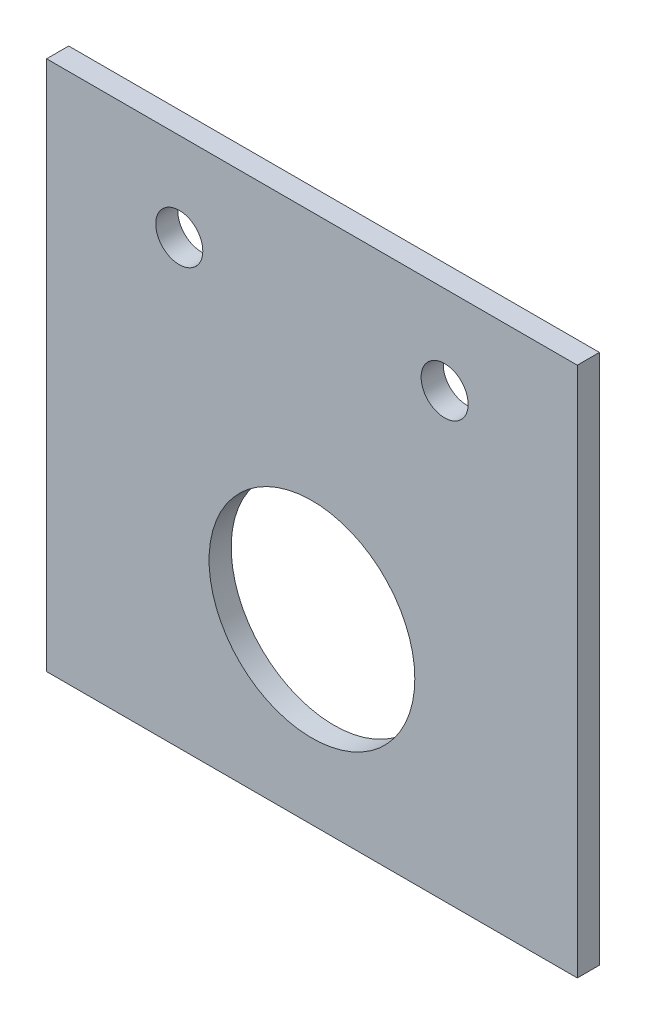
SolidWorks part; units mm, degrees
ref_plane "Front Plane" through (0, 0, 0) normal (0, 0, 1) x (1, 0, 0)
ref_plane "Top Plane" through (0, 0, 0) normal (0, 1, 0) x (1, 0, 0)
ref_plane "Right Plane" through (0, 0, 0) normal (1, 0, 0) x (0, 0, -1)
sketch "Sketch1" plane through (0, 0, 0) normal (0, 0, 1) x (1, 0, 0)
  line L1 (38.1, -38.1) -> (-38.1, -38.1)
  line L2 (38.1, -38.1) -> (38.1, 38.1)
  line L3 (38.1, 38.1) -> (-38.1, 38.1)
  line L4 (-38.1, -38.1) -> (-38.1, 38.1)
  line L5 (38.1, -38.1) -> (-38.1, 38.1) construction
  line L6 (38.1, 38.1) -> (-38.1, -38.1) construction
  point P0 (0, 0)
  dimension "D1" = 76.2
  dimension "D2" = 76.2
extrude "Boss-Extrude1" add sketch "Sketch1" along normal blind 3.175
hole_wizard "1/4 Clearance Hole1" positions "Sketch2" profile "Sketch3" hole size "1/4" standard "ANSI Inch" end condition through all
sketch "Sketch2" plane through (0, 0, 3.175) normal (0, 0, 1) x (1, 0, 0)
  line L0 (-38.1, 25.4) -> (38.1, 25.4) construction
  line L1 (-38.1, 38.1) -> (-38.1, -38.1) construction
  line L2 (38.1, -38.1) -> (38.1, 38.1) construction
  point P10 (-19.05, 25.4)
  point P12 (19.05, 25.4)
  dimension "D1" = 12.7
  dimension "D2" = 19.05
  dimension "D3" = 19.05
sketch "Sketch3" plane through (19.05, 25.4, 3.175) normal (1, 0, 0) x (0, -1, 0)
  line L0 (0, 0) -> (0, 3.175)
  line L1 (0, 3.175) -> (3.3782, 3.175)
  line L2 (3.3782, 3.175) -> (3.3782, 0)
  line L5 (3.3782, 0) -> (0, 0)
  line L11 (0, -6.35) -> (0, 107.95) construction
  dimension "Thru Hole Dia." = 6.7564
  dimension "Thru Hole Depth" = 3.175
sketch "Sketch4" plane through (0, 0, 3.175) normal (0, 0, 1) x (1, 0, 0)
  circle A0 centre (0, -12.5522) radius 14.77
  point P2 (0, -12.5522)
  dimension "D1" = 29.54
extrude "Cut-Extrude1" cut sketch "Sketch4" against normal through all and the other way through all
